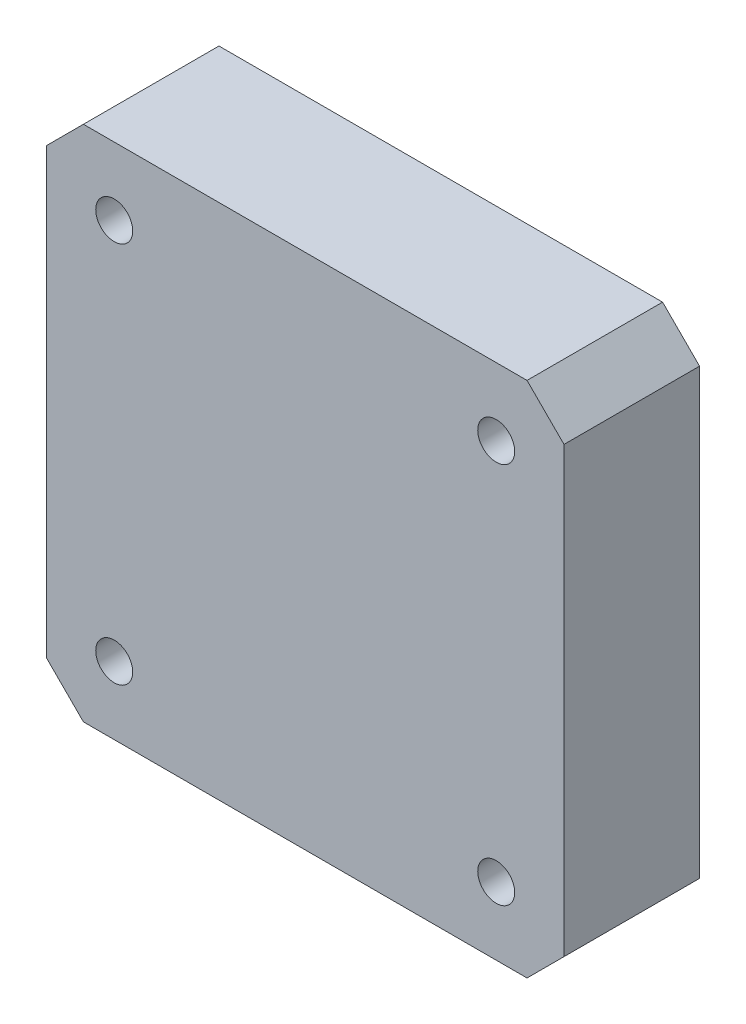
SolidWorks part; units mm, degrees
ref_plane "Front Plane" through (0, 0, 0) normal (0, 0, 1) x (1, 0, 0)
ref_plane "Top Plane" through (0, 0, 0) normal (0, 1, 0) x (1, 0, 0)
ref_plane "Right Plane" through (0, 0, 0) normal (1, 0, 0) x (0, 0, -1)
sketch "Sketch1" plane through (0, 0, 0) normal (0, 0, 1) x (1, 0, 0)
  line L1 (-21, 21) -> (21, 21)
  line L2 (-21, 21) -> (-21, -21)
  line L3 (-21, -21) -> (21, -21)
  line L4 (21, 21) -> (21, -21)
  line L5 (-21, 21) -> (21, -21) construction
  line L6 (-21, -21) -> (21, 21) construction
  point P0 (0, 0)
  dimension "D1" = 42
  dimension "D2" = 42
extrude "Boss-Extrude1" add sketch "Sketch1" along normal blind 11 contours L1 L4 L3 L2
chamfer "Chamfer1" distance 3 angle 45 4 edges at (21, -21, 5.5) (-21, -21, 5.5) (-21, 21, 5.5) (21, 21, 5.5)
sketch "Sketch3" plane through (0, 0, 0) normal (0, 0, -1) x (-1, 0, 0)
  circle A0 centre (0, 0) radius 16
  dimension "D1" = 32
sketch "Sketch4" plane through (0, 0, 0) normal (0, 0, -1) x (-1, 0, 0)
  circle A0 centre (0, 0) radius 11.25
  dimension "D1" = 22.5
extrude "Boss-Extrude2" add sketch "Sketch4" against normal blind 0.5
sketch "Sketch8" plane through (0, 0, 0) normal (0, 0, -1) x (-1, 0, 0)
  circle A4 centre (15.5, 15.5) radius 1.5
  circle A5 centre (-15.5, 15.5) radius 1.5
  circle A6 centre (-15.5, -15.5) radius 1.5
  circle A7 centre (15.5, -15.5) radius 1.5
  dimension "D1" = 31
  dimension "D2" = 31
  dimension "D4" = 3
  dimension "D3" = 15.5
  dimension "D5" = 15.5
extrude "Cut-Extrude4" cut sketch "Sketch8" against normal up to next
